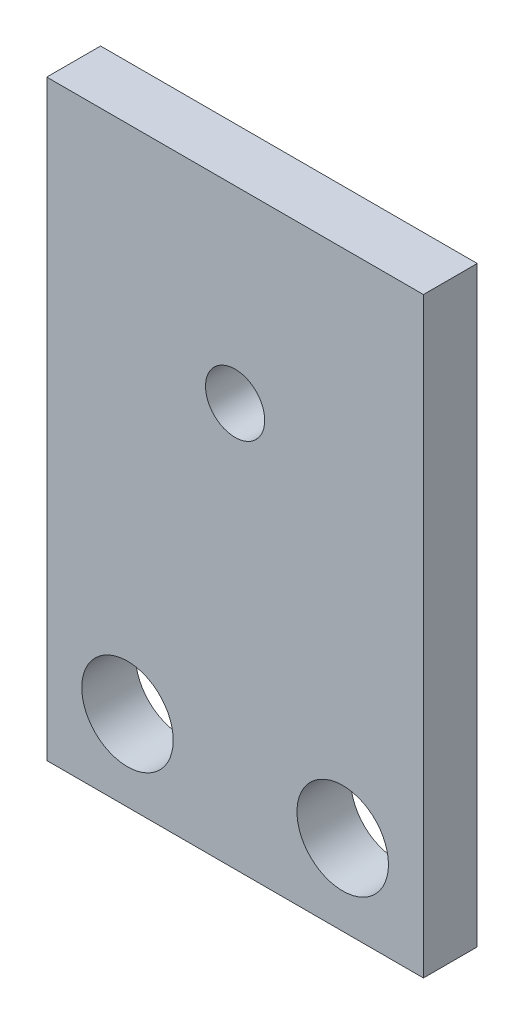
SolidWorks part; units mm, degrees
ref_plane "Спереди" through (0, 0, 0) normal (0, 0, 1) x (1, 0, 0)
ref_plane "Сверху" through (0, 0, 0) normal (0, 1, 0) x (1, 0, 0)
ref_plane "Справа" through (0, 0, 0) normal (1, 0, 0) x (0, 0, -1)
sketch "Эскиз1" plane through (0, 0, 0) normal (0, 0, 1) x (1, 0, 0)
  line L0 (-6.8356, 3) -> (22.8433, 3) construction
  line L1 (0, 0) -> (14, 0)
  line L2 (0, 0) -> (0, 22)
  line L3 (0, 22) -> (14, 22)
  line L4 (14, 0) -> (14, 22)
  circle A0 centre (3, 3) radius 1.7
  circle A1 centre (11, 3) radius 1.7
  circle A2 centre (7, 15) radius 1.1
  dimension "D4" = 8
  dimension "D5" = 3
  dimension "D6" = 12
  dimension "D7" = 7
  dimension "D8" = 3.4
  dimension "D9" = 3.4
  dimension "D10" = 2.2
  dimension "D1" = 14
  dimension "D2" = 22
  dimension "D3" = 3
extrude "Вытянуть1" add sketch "Эскиз1" along normal blind 2
cosmetic thread "Условное изображение резьбы1" parameters "D1"=2, "D2"=3
